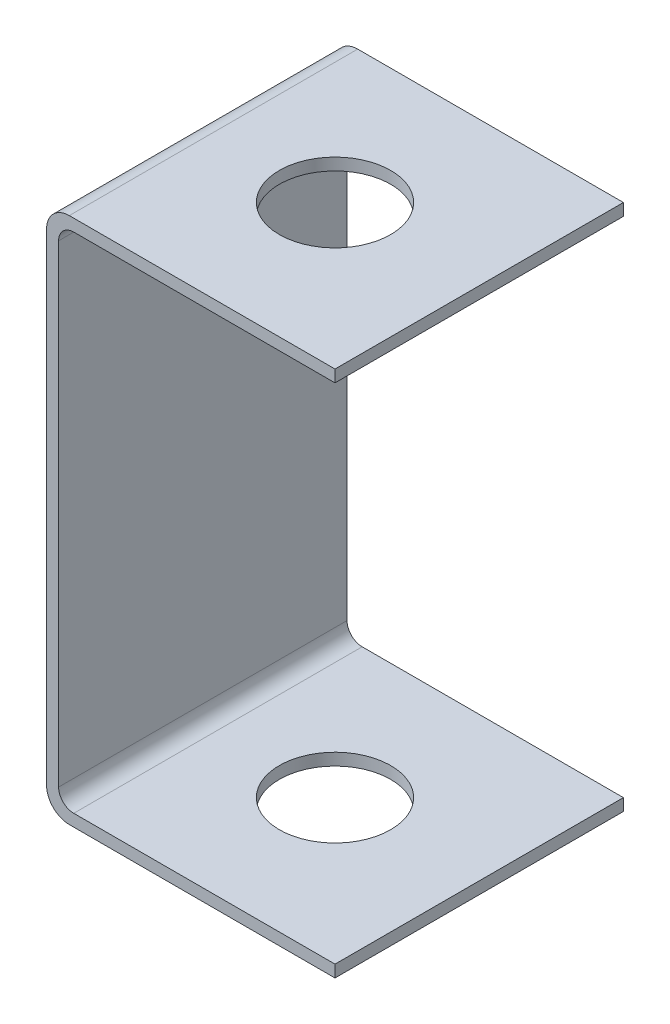
SolidWorks part; units mm, degrees
material "Alumina"
ref_plane "Front Plane" through (0, 0, 0) normal (0, 0, 1) x (1, 0, 0)
ref_plane "Top Plane" through (0, 0, 0) normal (0, 1, 0) x (1, 0, 0)
ref_plane "Right Plane" through (0, 0, 0) normal (1, 0, 0) x (0, 0, -1)
sketch "Sketch1" plane through (0, 0, 0) normal (0, 0, 1) x (1, 0, 0)
  line L0 (-17.4625, 68.0875) -> (19.05, 68.0875)
  line L1 (19.05, 68.0875) -> (19.05, 69.675)
  line L2 (19.05, 69.675) -> (-19.05, 69.675)
  line L3 (-19.05, 69.675) -> (-19.05, 0)
  line L4 (-19.05, 0) -> (19.05, 0)
  line L5 (19.05, 0) -> (19.05, 1.5875)
  line L6 (19.05, 1.5875) -> (-17.4625, 1.5875)
  line L7 (-17.4625, 1.5875) -> (-17.4625, 68.0875)
  point P7 (0, 0)
  dimension "D1" = 1.5875
  dimension "D2" = 1.5875
  dimension "D3" = 1.5875
  dimension "D4" = 38.1
  dimension "D5" = 66.5
extrude "Boss-Extrude1" add sketch "Sketch1" along normal blind 38.1
sketch "Sketch3" plane through (0, 0, 0) normal (0, 1, 0) x (1, 0, 0)
  circle A0 centre (0, -19.05) radius 7.35
  dimension "D2" = 14.7
  dimension "D1" = 19.05
extrude "Cut-Extrude1" cut sketch "Sketch3" along normal through all
fillet "Fillet1" radius 2 2 edges at (-17.4625, 1.5875, 19.05) (-17.4625, 68.0875, 19.05)
fillet "Fillet2" radius 3 2 edges at (-19.05, 0, 19.05) (-19.05, 69.675, 19.05)
equation "\"boltDiameter\"= 1in / 2"
equation "\"sleeveHeight\"= 2.5in"
equation "\"bracketThickness\"= 1in / 16"
equation "\"D1@Sketch1\"=\"bracketThickness\""
equation "\"D2@Sketch1\"=\"bracketThickness\""
equation "\"D3@Sketch1\"=\"bracketThickness\""
equation "\"D5@Sketch1\"=\"sleeveHeight\"+3mm"
equation "\"D2@Sketch3\"=\"boltDiameter\"+2mm"
